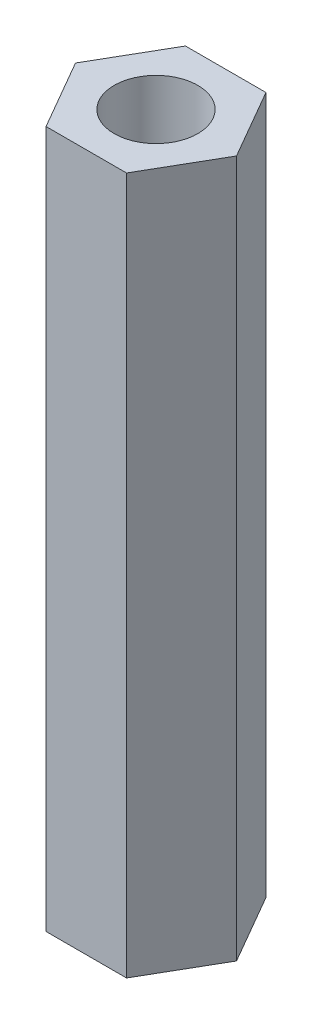
SolidWorks part; units mm, degrees
ref_plane "Front Plane" through (0, 0, 0) normal (0, 0, 1) x (1, 0, 0)
ref_plane "Top Plane" through (0, 0, 0) normal (0, 1, 0) x (1, 0, 0)
ref_plane "Right Plane" through (0, 0, 0) normal (1, 0, 0) x (0, 0, -1)
sketch "Sketch1" plane through (0, 0, 0) normal (0, 1, 0) x (1, 0, 0)
  line L1 (2.8868, 0) -> (1.4434, 2.5)
  line L2 (1.4434, 2.5) -> (-1.4434, 2.5)
  line L3 (-1.4434, 2.5) -> (-2.8868, 0)
  line L4 (-2.8868, 0) -> (-1.4434, -2.5)
  line L5 (-1.4434, -2.5) -> (1.4434, -2.5)
  line L6 (1.4434, -2.5) -> (2.8868, 0)
  circle A0 centre (0, 0) radius 2.5 construction
  dimension "D1" = 5
extrude "Boss-Extrude1" add sketch "Sketch1" along normal blind 25
sketch "Sketch2" plane through (0, 25, 0) normal (0, 1, 0) x (1, 0, 0)
  circle A0 centre (0, 0) radius 1.5
  dimension "D1" = 3
extrude "Cut-Extrude1" cut sketch "Sketch2" against normal blind 25
